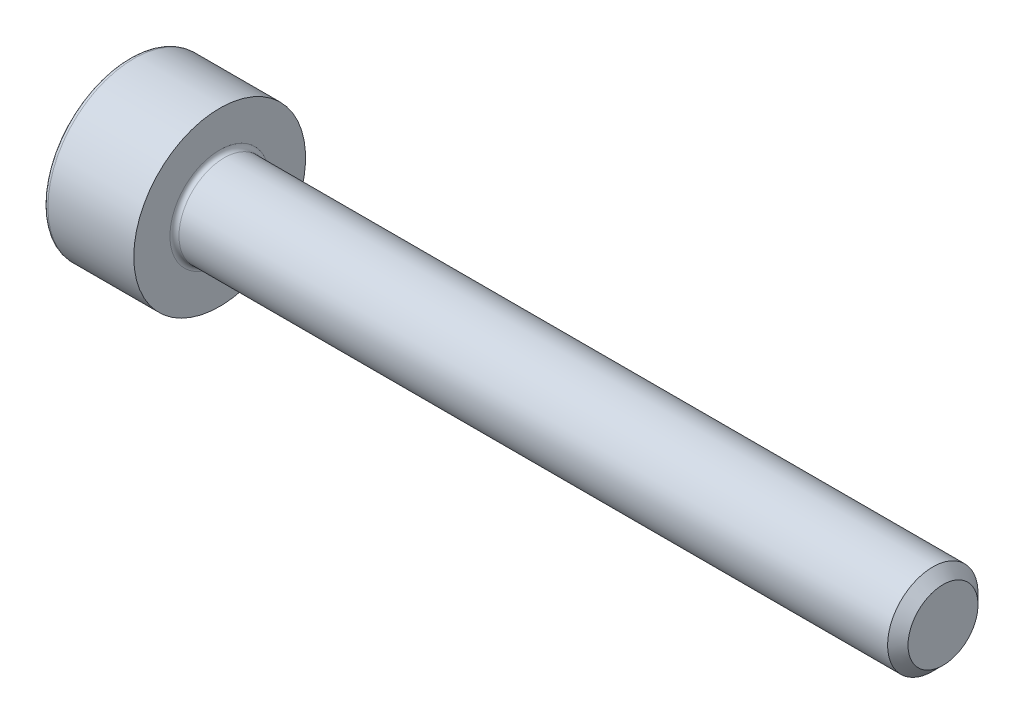
SolidWorks part; units mm, degrees
revolve "Base-Revolve" add sketch "BodySke"
sketch "BodySke" plane through (0, 0, 0) normal (0, 0, 1) x (1, 0, 0)
  line L0 (0, 0) -> (0, 1.9)
  line L1 (0, 1.9) -> (2, 1.9)
  line L2 (2, 1.9) -> (2, 1)
  line L3 (2, 1) -> (17.774, 1)
  line L4 (18, 0.774) -> (18, 0)
  line L5 (18, 0) -> (0, 0)
  line L6 (-31.75, 0) -> (127, 0) construction
  line L8 (18, 0.774) -> (17.774, 1)
  line L10 (18, -0.774) -> (17.774, -1) construction
  line L11 (2.4, 9.525) -> (2.4, 3.175) construction
  line L12 (2, 9.525) -> (2, 3.175) construction
  line L13 (-42, 9.525) -> (-42, 3.175) construction
  dimension "Head_ht" = 2
  dimension "Length" = 16
  dimension "Body_ch_ang" = 45
  dimension "Diameter" = 2
  dimension "Minor_dia" = 1.548
  dimension "Advance" = 0.4
  dimension "Thread_nom" = 16
  dimension "Thread_length" = 60
  dimension "Head_dia" = 3.8
cosmetic thread "ThreadCosmetic" [suppressed]
fillet "Fillet1" radius 0.1 1 edges at (2, 0, 1)
fillet "Fillet2" radius 0.1 1 edges at (0, 0, 1.9)
ref_plane "Plane1" through (0, 0, 0) normal (0, 0, 1) x (1, 0, 0)
ref_plane "Plane2" through (0, 0, 0) normal (0, 1, 0) x (1, 0, 0)
ref_plane "Plane3" through (0, 0, 0) normal (1, 0, 0) x (0, 0, -1)
other "Configuration Table"
sketch "Sketch2" plane through (0, 0, 0) normal (0, 0, 1) x (1, 0, 0)
  line L0 (0, 0.7725) -> (1, 0.7725)
  line L1 (1, 0.7725) -> (1.446, 0)
  line L2 (-31.75, 0) -> (127, 0) construction
  line L3 (1.446, 0) -> (0, 0)
  line L4 (0, 0) -> (0, 0.7725)
  line L6 (0, 0) -> (47.625, 0) construction
  dimension "D1" = 0.7725
  dimension "D2" = 60
  dimension "Depth" = 1
revolve "Hex-PreBroach" cut sketch "Sketch2" angle 360 about L6
sketch "Sketch3" plane through (0, 0, 0) normal (-1, 0, 0) x (0, 0.5, 0.866)
  line L0 (0.446, 0.7725) -> (-0.446, 0.7725)
  line L1 (-0.446, 0.7725) -> (-0.892, 0)
  line L2 (0.446, 0.7725) -> (0.892, 0)
  line L3 (0.446, -0.7725) -> (0.892, 0)
  line L4 (0.446, -0.7725) -> (-0.446, -0.7725)
  line L5 (-0.446, -0.7725) -> (-0.892, 0)
  dimension "D1" = 0.7725
  dimension "D2" = 0.7725
  dimension "Hex_size" = 1.545
extrude "Hex" cut sketch "Sketch3" against normal blind 1
sketch "ThdSchSke" plane through (0, 0, 0) normal (0, 0, 1) x (1, 0, 0)
  line L0 (3.2, -0.774) -> (3.0418, -1)
  line L1 (3.2, -0.774) -> (3.3582, -1)
  line L2 (3.3582, -1) -> (3.3582, -1.25)
  line L3 (-3.175, 0) -> (5.1513, 0) construction
  line L4 (0, 1.8) -> (0, -1.8) construction
  line L5 (3.3582, -1.25) -> (3.0418, -1.25)
  line L6 (3.0418, -1.25) -> (3.0418, -1)
  dimension "Thread_minor" = 1.548
  dimension "Diameter" = 2
  dimension "Start" = 3.2
revolve "ThreadSchematic" [suppressed] cut sketch "ThdSchSke" angle 360 about L3
pattern_linear "ThdSchPat" [suppressed]
equation "\"D2@Sketch3\" = \"Hex_size@Sketch3\" / 2"
equation "\"D1@Sketch3\" = \"Hex_size@Sketch3\" / 2"
equation "\"D1@Sketch2\" = \"Hex_size@Sketch3\" / 2"
equation "\"Thread_minor@ThreadCosmetic\"  =  \"Minor_dia@BodySke\""
equation "\"Depth@Sketch2\" =  \"Key_eng@Hex\""
equation "\"Thread_length@ThreadCosmetic\" = ((sgn( (\"Length@BodySke\" - \"Advance@BodySke\" * 3.0) - \"Thread_nom@BodySke\" )-1)*( (\"Length@BodySke\" - \"Advance@BodySke\" * 3.0) - \"Thread_nom@BodySke\" ))/-2+ \"Thread_nom@BodySke\""
equation "\"Thread_minor@ThdSchSke\" = \"Minor_dia@BodySke\""
equation "\"Diameter@ThdSchSke\" = \"Diameter@BodySke\""
equation "\"Overcut@ThdSchSke\" = \"Diameter@BodySke\" * 1.25"
equation "\"Start@ThdSchSke\" = \"Head_ht@BodySke\" + \"Length@BodySke\" - \"Thread_length@ThreadCosmetic\"  '---Non-countersunk---"
equation "\"Num_threads@ThdSchPat\" = int( \"Thread_length@ThreadCosmetic\" / \"Advance@BodySke\" + 0.999 )  + 1"
equation "\"Advance@ThdSchPat\" = \"Thread_length@ThreadCosmetic\" /  (\"Num_threads@ThdSchPat\" - 1) 'relax it"
equation "\"Num_threads@ThdSchPat\" = \"Num_threads@ThdSchPat\" - sgn( \"Num_threads@ThdSchPat\" - 1) '---chamfered tips only---"
